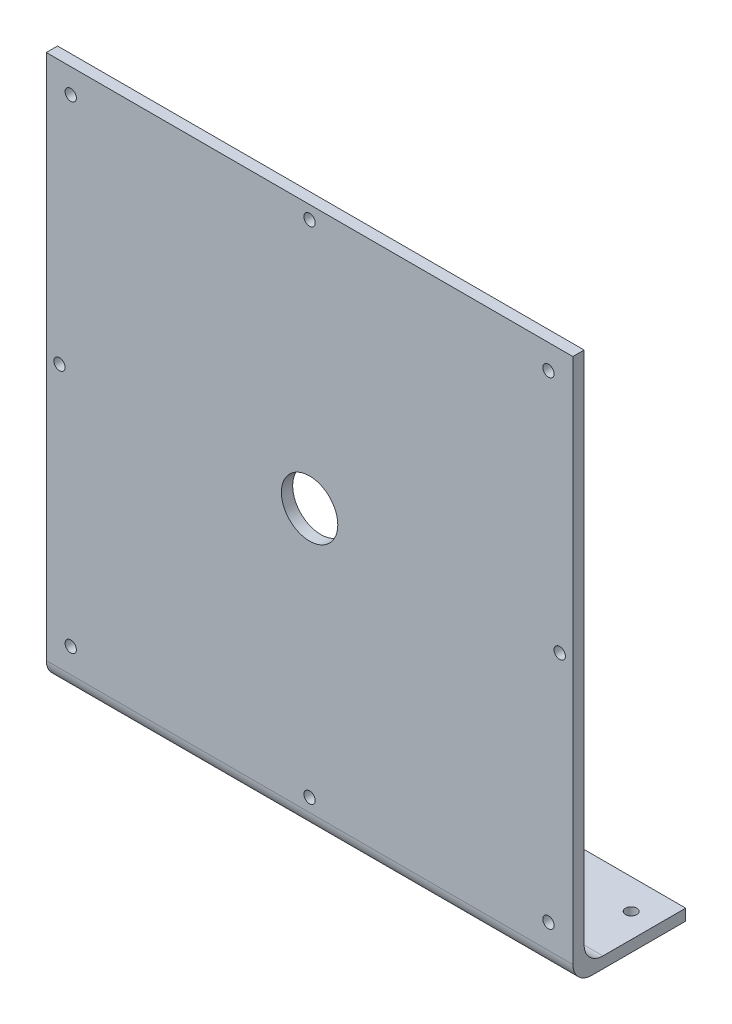
SolidWorks part; units mm, degrees
ref_plane "Přední rovina" through (0, 0, 0) normal (0, 0, 1) x (1, 0, 0)
ref_plane "Horní rovina" through (0, 0, 0) normal (0, 1, 0) x (1, 0, 0)
ref_plane "Pravá rovina" through (0, 0, 0) normal (1, 0, 0) x (0, 0, -1)
sketch "Skica1" plane through (0, 0, 0) normal (0, 0, 1) x (1, 0, 0)
  line L0 (0, 0) -> (0, 72.5) construction
  line L1 (-70, -72.5) -> (70, -72.5)
  line L2 (-70, -72.5) -> (-70, 72.5)
  line L3 (-70, 72.5) -> (70, 72.5)
  line L4 (70, -72.5) -> (70, 72.5)
  line L5 (-70, -72.5) -> (70, 72.5) construction
  line L6 (-70, 72.5) -> (70, -72.5) construction
  line L7 (-70, 2.5) -> (0, 2.5) construction
  circle A0 centre (-63.5, 66) radius 1.5
  circle A1 centre (-66.5, 2.5) radius 1.5
  circle A2 centre (63.5, 66) radius 1.5
  circle A5 centre (66.5, 2.5) radius 1.5
  circle A6 centre (63.5, -61) radius 1.5
  circle A7 centre (-63.5, -61) radius 1.5
  point P0 (0, 0)
  dimension "D3" = 3
  dimension "D1" = 140
  dimension "D2" = 145
  dimension "D4" = 63.5
  dimension "D5" = 127
  dimension "D6" = 3.5
  dimension "D7" = 6.5
extrude "Přidat vysunutím1" add sketch "Skica1" along normal blind 3
sketch "Skica2" plane through (0, -72.5, 0) normal (0, -1, 0) x (1, 0, 0)
  line L0 (70, 3) -> (70, 0) construction
  line L1 (-70, 3) -> (70, 3)
  line L2 (-70, 3) -> (-70, -27)
  line L3 (-70, -27) -> (70, -27)
  line L4 (70, 3) -> (70, -27)
  dimension "D1" = 30
extrude "Přidat vysunutím2" add sketch "Skica2" against normal blind 3
sketch "Skica3" plane through (0, -69.5, 0) normal (0, 1, 0) x (1, 0, 0)
  line L0 (0, 0) -> (0, 27) construction
  line L1 (70, 0) -> (-70, 0) construction
  line L2 (-70, 27) -> (70, 27) construction
  line L3 (-70, 0) -> (-70, 27) construction
  circle A0 centre (-63.5, 19) radius 1.5
  circle A1 centre (63.5, 19) radius 1.5
  dimension "D1" = 3
  dimension "D2" = 6.5
  dimension "D3" = 8
extrude "Odebrat vysunutím1" cut sketch "Skica3" against normal through all
fillet "Zaoblit1" radius 5 2 edges at (0, -72.5, 3) (0, -69.5, 0)
sketch "Skica4" plane through (0, 0, 3) normal (0, 0, 1) x (1, 0, 0)
  line L0 (-66.5, 2.5) -> (66.5, 2.5) construction
  line L1 (70, 72.5) -> (-70, 72.5) construction
  circle A0 centre (0, 2.5) radius 7.5
  circle A1 centre (0, 69) radius 1.5
  circle A2 centre (-63.5, 66) radius 1.5 construction
  circle A3 centre (0, -64) radius 1.5
  dimension "D1" = 15
  dimension "D2" = 3.5
extrude "Odebrat vysunutím2" cut sketch "Skica4" against normal through all
